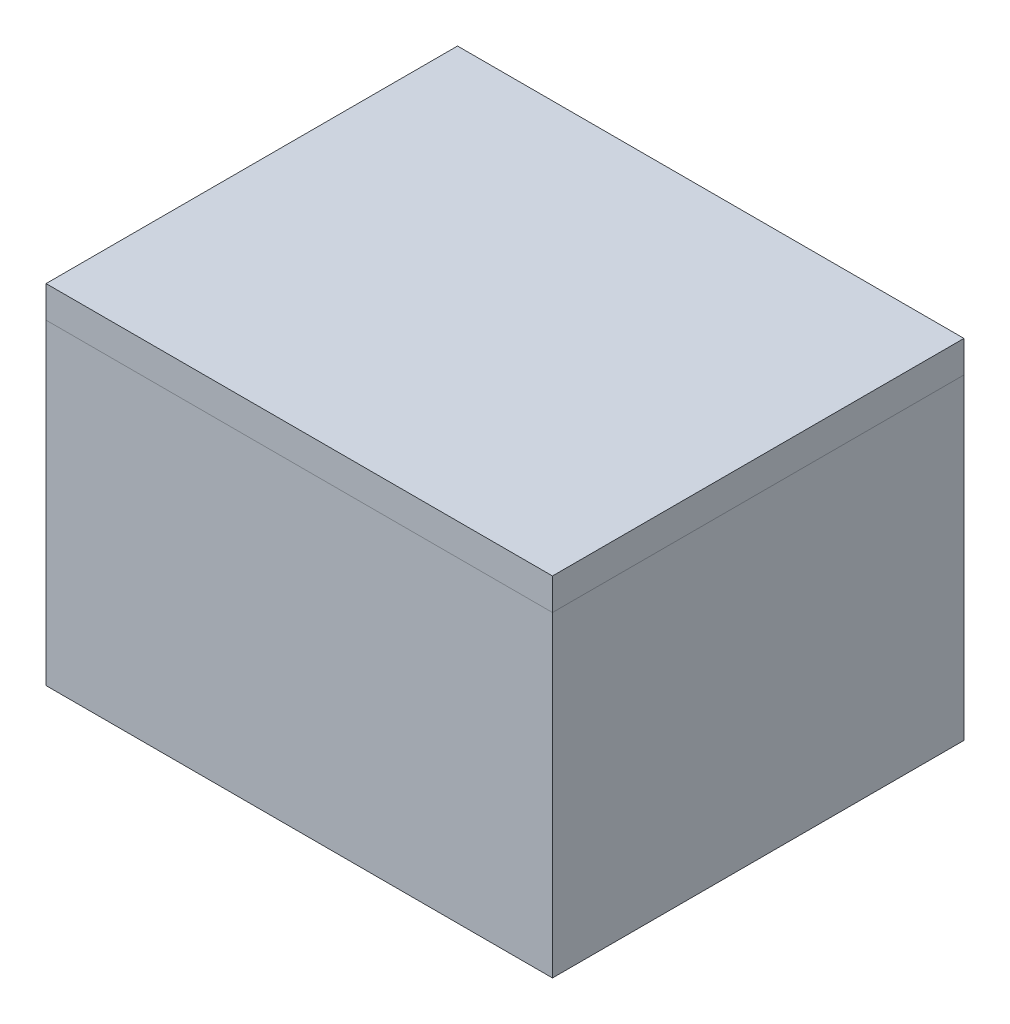
SolidWorks part; units mm, degrees
material "Glass"
ref_plane "Front Plane" through (0, 0, 0) normal (0, 0, 1) x (1, 0, 0)
ref_plane "Top Plane" through (0, 0, 0) normal (0, 1, 0) x (1, 0, 0)
ref_plane "Right Plane" through (0, 0, 0) normal (1, 0, 0) x (0, 0, -1)
sketch "Sketch1" plane through (0, 0, 0) normal (0, 1, 0) x (1, 0, 0)
  line L1 (-101.6, -82.55) -> (101.6, -82.55)
  line L2 (-101.6, -82.55) -> (-101.6, 82.55)
  line L3 (-101.6, 82.55) -> (101.6, 82.55)
  line L4 (101.6, -82.55) -> (101.6, 82.55)
  line L5 (-101.6, -82.55) -> (101.6, 82.55) construction
  line L6 (-101.6, 82.55) -> (101.6, -82.55) construction
  point P0 (0, 0)
  dimension "D1" = 165.1
  dimension "D2" = 203.2
extrude "Boss-Extrude1" add sketch "Sketch1" along normal blind 12.7
sketch "Sketch2" plane through (0, 0, 0) normal (0, -1, 0) x (1, 0, 0)
  line L8 (88.9, -69.85) -> (88.9, 69.85)
  line L9 (88.9, 69.85) -> (-88.9, 69.85)
  line L10 (-88.9, 69.85) -> (-88.9, -69.85)
  line L11 (-88.9, -69.85) -> (88.9, -69.85)
  line L12 (88.9, -69.85) -> (88.9, 69.85)
  line L13 (88.9, 69.85) -> (-88.9, 69.85)
  line L14 (-88.9, 69.85) -> (-88.9, -69.85)
  line L15 (-88.9, -69.85) -> (88.9, -69.85)
  line M5 (101.6, -82.55) -> (101.6, 82.55)
  line M6 (101.6, 82.55) -> (-101.6, 82.55)
  line M7 (-101.6, 82.55) -> (-101.6, -82.55)
  line M8 (-101.6, -82.55) -> (101.6, -82.55)
  dimension "D1" = 12.7
extrude "Boss-Extrude2" add sketch "Sketch2" along normal blind 127 separate body contours L15 L14 L13 L12 M8 M5 M6 M7
